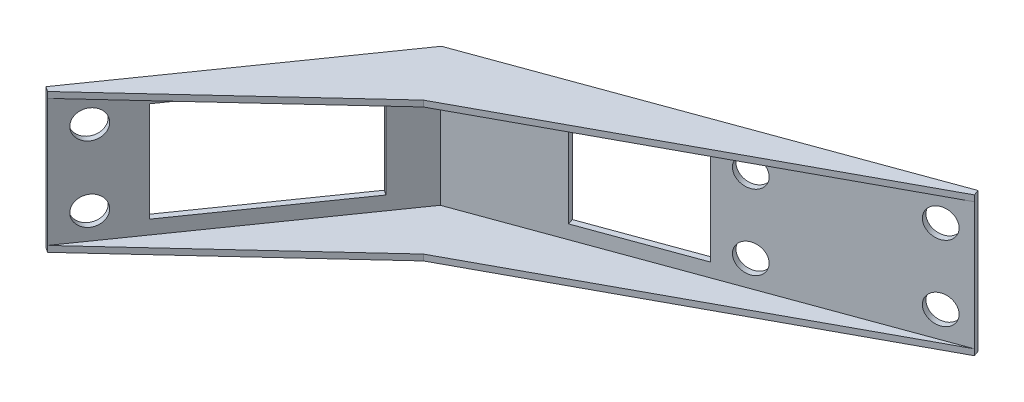
SolidWorks part; units mm, degrees
material "AISI 1020"
ref_plane "Front Plane" through (0, 0, 0) normal (0, 0, 1) x (1, 0, 0)
ref_plane "Top Plane" through (0, 0, 0) normal (0, 1, 0) x (1, 0, 0)
ref_plane "Right Plane" through (0, 0, 0) normal (1, 0, 0) x (0, 0, -1)
sketch "Sketch1" plane through (0, 0, 0) normal (0, 1, 0) x (1, 0, 0)
  line L0 (65.7405, 35.769) -> (-16.1556, 5.8995)
  line L1 (-49.9781, -42.47) -> (-16.1556, 5.8995)
  line L2 (-49.9781, -42.47) -> (-51.0025, -41.7537)
  line L3 (-51.0025, -41.7537) -> (-16.9541, 6.9388)
  line L4 (65.7405, 35.769) -> (65.3122, 36.9433)
  line L5 (65.3122, 36.9433) -> (-16.9541, 6.9388)
extrude "Boss-Extrude1" add sketch "Sketch1" along normal blind 26.65
sketch "Sketch2" plane through (0, 26.65, 0) normal (0, 1, 0) x (1, 0, 0)
  line L0 (-51.0025, -41.7537) -> (-49.9781, -42.47)
  line L1 (-51.0025, -41.7537) -> (-16.9541, 6.9388)
  line L2 (-16.9541, 6.9388) -> (65.3122, 36.9433)
  line L3 (65.3122, 36.9433) -> (65.7405, 35.769)
  line L6 (65.7405, 35.769) -> (-7.8775, -6.4859)
  line L7 (-7.8775, -6.4859) -> (-49.9781, -42.47)
extrude "Boss-Extrude2" add sketch "Sketch2" along normal blind 1.25
sketch "Sketch3" plane through (0, 0, 0) normal (0, -1, 0) x (1, 0, 0)
  line L0 (65.3122, -36.9433) -> (65.7405, -35.769)
  line L1 (65.7405, -35.769) -> (-7.8775, 6.4859)
  line L2 (-7.8775, 6.4859) -> (-49.9781, 42.47)
  line L3 (-49.9781, 42.47) -> (-51.0025, 41.7537)
  line L4 (-51.0025, 41.7537) -> (-16.9541, -6.9388)
  line L5 (-16.9541, -6.9388) -> (65.3122, -36.9433)
extrude "Boss-Extrude3" add sketch "Sketch3" along normal blind 1.25
sketch "Sketch4" plane through (-4.2241, 0, -11.5817) normal (-0.3426, 0, -0.9395) x (-0.9395, 0, 0.3426)
  line L0 (-74.0169, 26.65) -> (-74.0169, 21.15) construction
  line L1 (-74.0169, 27.9) -> (-74.0169, -1.25) construction
  line L2 (-74.0169, 21.15) -> (-68.5169, 21.15) construction
  line L3 (-68.5169, 21.15) -> (-37.5169, 21.15) construction
  line L4 (-74.0169, 0) -> (-74.0169, 5.5) construction
  line L5 (-74.0169, 5.5) -> (-68.5169, 5.5) construction
  line L6 (-68.5169, 5.5) -> (-37.5169, 5.5) construction
  circle A0 centre (-68.5169, 21.15) radius 3
  circle A1 centre (-37.5169, 21.15) radius 3
  circle A2 centre (-37.5169, 5.5) radius 3
  circle A3 centre (-68.5169, 5.5) radius 3
extrude "Cut-Extrude1" cut sketch "Sketch4" against normal blind 1.25
sketch "Sketch5" plane through (-14.6452, 0, -10.2407) normal (-0.8195, 0, -0.5731) x (-0.5731, 0, 0.8195)
  line L0 (63.445, 0) -> (63.445, 5.5) construction
  line L1 (63.445, 27.9) -> (63.445, -1.25) construction
  line L2 (63.445, 5.5) -> (57.095, 5.5) construction
  line L3 (63.445, 26.65) -> (63.445, 21.15) construction
  line L4 (63.445, 21.15) -> (57.095, 21.15) construction
  circle A0 centre (57.095, 21.15) radius 3
  circle A1 centre (57.095, 5.5) radius 3
extrude "Cut-Extrude2" cut sketch "Sketch5" against normal blind 1.25
sketch "Sketch6" plane through (-14.6452, 0, -10.2407) normal (-0.8195, 0, -0.5731) x (-0.5731, 0, 0.8195)
  line L0 (4.0291, 13.325) -> (53.9905, 13.325) construction
  line L1 (4.0291, 27.9) -> (4.0291, -1.25) construction
  line L3 (12.6096, 2.8742) -> (48.0789, 2.8742)
  line L4 (12.6096, 2.8742) -> (12.6096, 23.7758)
  line L5 (12.6096, 23.7758) -> (48.0789, 23.7758)
  line L6 (48.0789, 2.8742) -> (48.0789, 23.7758)
  line L7 (12.6096, 2.8742) -> (48.0789, 23.7758) construction
  line L8 (12.6096, 23.7758) -> (48.0789, 2.8742) construction
  point P4 (30.3442, 13.325)
extrude "Cut-Extrude3" cut sketch "Sketch6" against normal blind 1.25
sketch "Sketch7" plane through (-4.2241, 0, -11.5817) normal (-0.3426, 0, -0.9395) x (-0.9395, 0, 0.3426)
  line L0 (13.5502, 13.325) -> (-43.4808, 13.325) construction
  line L1 (13.5502, 27.9) -> (13.5502, -1.25) construction
  line L2 (-13.7996, 23.7758) -> (-7.7996, 23.7758)
  line L3 (-30.9288, 2.8742) -> (-13.7996, 2.8742)
  line L4 (-30.9288, 2.8742) -> (-30.9288, 23.7758)
  line L5 (-30.9288, 23.7758) -> (-13.7996, 23.7758)
  line L7 (-30.9288, 2.8742) -> (-13.7996, 23.7758) construction
  line L8 (-30.9288, 23.7758) -> (-13.7996, 2.8742) construction
  line L9 (-7.7996, 23.7758) -> (-7.7996, 2.8742)
  line L10 (-7.7996, 2.8742) -> (-13.7996, 2.8742)
  point P4 (-22.3642, 13.325)
extrude "Cut-Extrude4" cut sketch "Sketch7" against normal blind 1.25
sketch "Sketch8" plane through (0, -1.25, 0) normal (0, -1, 0) x (1, 0, 0)
  line L1 (65.7405, -35.769) -> (-9.0828, 4.7031)
  line L2 (-9.0828, 4.7031) -> (-49.9781, 42.47)
  line L3 (-49.9781, 42.47) -> (-7.8775, 6.4859)
  line L4 (-7.8775, 6.4859) -> (65.7405, -35.769)
extrude "Cut-Extrude5" cut sketch "Sketch8" against normal blind 41.25
